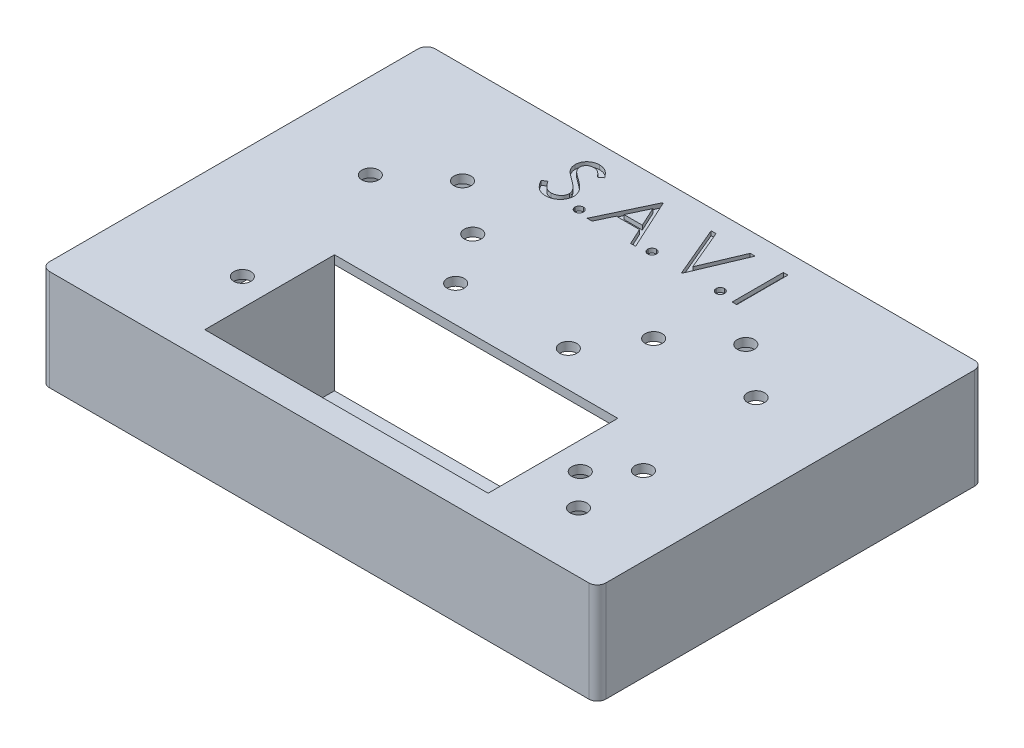
SolidWorks part; units mm, degrees
ref_plane "Front Plane" through (0, 0, 0) normal (0, 0, 1) x (1, 0, 0)
ref_plane "Top Plane" through (0, 0, 0) normal (0, 1, 0) x (1, 0, 0)
ref_plane "Right Plane" through (0, 0, 0) normal (1, 0, 0) x (0, 0, -1)
sketch "Sketch1" plane through (0, 0, 0) normal (0, 1, 0) x (1, 0, 0)
  line L1 (-81.5, 56.5) -> (81.5, 56.5)
  line L2 (-81.5, 56.5) -> (-81.5, -56.5)
  line L3 (-81.5, -56.5) -> (81.5, -56.5)
  line L4 (81.5, 56.5) -> (81.5, -56.5)
  line L5 (-81.5, 56.5) -> (81.5, -56.5) construction
  line L6 (-81.5, -56.5) -> (81.5, 56.5) construction
  point P0 (0, 0)
  dimension "D1" = 113
  dimension "D2" = 163
extrude "Boss-Extrude1" add sketch "Sketch1" along normal blind 29.5
fillet "Fillet1" radius 2.5 4 edges at (81.5, 14.75, -56.5) (-81.5, 14.75, -56.5) (-81.5, 14.75, 56.5) (81.5, 14.75, 56.5)
sketch "Sketch2" plane through (0, 0, 0) normal (0, -1, 0) x (1, 0, 0)
  line L1 (-77.5, 52.5) -> (77.5, 52.5)
  line L2 (-77.5, 52.5) -> (-77.5, -52.5)
  line L3 (-77.5, -52.5) -> (77.5, -52.5)
  line L4 (77.5, 52.5) -> (77.5, -52.5)
  line L5 (-77.5, 52.5) -> (77.5, -52.5) construction
  line L6 (-77.5, -52.5) -> (77.5, 52.5) construction
  point P0 (0, 0)
  dimension "D1" = 105
  dimension "D2" = 155
extrude "Cut-Extrude1" cut sketch "Sketch2" against normal blind 27
sketch "Sketch3" plane through (0, 27, 0) normal (0, -1, 0) x (1, 0, 0)
  line L0 (77.5, 52.5) -> (-77.5, 52.5) construction
  line L1 (-45.5, 48.5) -> (45.5, 48.5)
  line L2 (-45.5, 48.5) -> (-45.5, 10.5)
  line L3 (-45.5, 10.5) -> (45.5, 10.5)
  line L4 (45.5, 48.5) -> (45.5, 10.5)
  line L5 (-77.5, 52.5) -> (-77.5, -52.5) construction
  dimension "D1" = 4
  dimension "D2" = 38
  dimension "D3" = 91
  dimension "D4" = 32
extrude "Boss-Extrude4" add sketch "Sketch3" along normal blind 35
sketch "Sketch6" plane through (0, 0, 10.5) normal (0, 0, -1) x (-1, 0, 0)
  line L0 (45.5, 27) -> (-45.5, 27) construction
  line L1 (41.5, 27) -> (-41.5, 27)
  line L2 (41.5, 27) -> (41.5, -5)
  line L3 (41.5, -5) -> (-41.5, -5)
  line L4 (-41.5, 27) -> (-41.5, -5)
  line L5 (45.5, -8) -> (-45.5, -8) construction
  line L6 (45.5, -8) -> (45.5, 27) construction
  dimension "D1" = 83
  dimension "D2" = 3
  dimension "D3" = 4
extrude "Cut-Extrude2" cut sketch "Sketch6" against normal blind 39
sketch "Sketch7" plane through (0, 27, 0) normal (0, -1, 0) x (1, 0, 0)
  line L1 (-41.5, 10.5) -> (41.5, 10.5)
  line L2 (-41.5, 10.5) -> (-41.5, 48.5)
  line L3 (-41.5, 48.5) -> (41.5, 48.5)
  line L4 (41.5, 10.5) -> (41.5, 48.5)
extrude "Cut-Extrude3" cut sketch "Sketch7" against normal blind 3
sketch "Sketch8" plane through (0, 29.5, 0) normal (0, 1, 0) x (1, 0, 0)
  line L0 (-41.5, -10.5) -> (-41.5, -48.5) construction
  line L1 (41.5, -48.5) -> (41.5, -10.5) construction
  line L2 (41.5, -48.5) -> (41.5, -10.5) construction
  line L3 (41.5, -48.5) -> (-41.5, -48.5) construction
  line L4 (41.5, -10.5) -> (-41.5, -10.5) construction
  line L5 (41.5, -10.5) -> (-41.5, -10.5) construction
  circle A0 centre (-49.5, -29.5) radius 2.5
  circle A1 centre (49.5, -29.5) radius 2.5
  circle A2 centre (58.5, -20) radius 2.5
  circle A3 centre (58.5, -39) radius 2.5
  circle A4 centre (-16.5, 0) radius 2.5
  circle A5 centre (16.5, 0) radius 2.5
  circle A6 centre (-56.5, 15) radius 2.5
  circle A7 centre (-41.5, 27) radius 2.5
  circle A8 centre (-26.5, 15) radius 2.5
  circle A9 centre (41.5, 27) radius 2.5
  circle A10 centre (26.5, 15) radius 2.5
  circle A11 centre (56.5, 15) radius 2.5
  dimension "D1" = 5
  dimension "D2" = 5
  dimension "D7" = 5
  dimension "D8" = 5
  dimension "D16" = 5
  dimension "D17" = 5
  dimension "D18" = 5
  dimension "D19" = 5
  dimension "D20" = 5
  dimension "D21" = 5
  dimension "D22" = 5
  dimension "D23" = 5
  dimension "D3" = 8
  dimension "D4" = 8
  dimension "D5" = 17
  dimension "D6" = 17
  dimension "D9" = 9.5
  dimension "D10" = 19
  dimension "D11" = 19
  dimension "D12" = 19
  dimension "D13" = 9.5
  dimension "D14" = 25
  dimension "D15" = 25
  dimension "D24" = 15
  dimension "D25" = 15
  dimension "D26" = 15
  dimension "D27" = 15
  dimension "D28" = 15
  dimension "D29" = 12
  dimension "D30" = 15
  dimension "D31" = 15
  dimension "D32" = 12
  dimension "D33" = 15
  dimension "D34" = 37.5
extrude "Cut-Extrude5" cut sketch "Sketch8" against normal blind 2.5
sketch "Sketch9" plane through (0, 29.5, 0) normal (0, 1, 0) x (1, 0, 0)
  line L1 (-81.5, 54) -> (-81.5, -54) construction
  text T0 "S.A.V.I" font "Century Gothic" height 15
  dimension "D1" = 51
extrude "Cut-Extrude6" cut sketch "Sketch9" against normal blind 1.25
sketch "Sketch10" plane through (0, 0, 0) normal (0, -1, 0) x (-1, 0, 0)
  line L0 (61.5, -54.5) -> (58.5, -54.5) construction
  line L1 (61.5, -55.5) -> (58.5, -55.5)
  line L2 (61.5, -53.5) -> (58.5, -53.5)
  line L3 (-61.5, -54.5) -> (-58.5, -54.5) construction
  line L4 (-61.5, -53.5) -> (-58.5, -53.5)
  line L5 (-61.5, -55.5) -> (-58.5, -55.5)
  line L6 (61.5, 54.5) -> (58.5, 54.5) construction
  line L7 (61.5, 53.5) -> (58.5, 53.5)
  line L8 (61.5, 55.5) -> (58.5, 55.5)
  line L9 (-61.5, 54.5) -> (-58.5, 54.5) construction
  line L10 (-61.5, 55.5) -> (-58.5, 55.5)
  line L11 (-61.5, 53.5) -> (-58.5, 53.5)
  line L12 (81.5, 54) -> (81.5, -54) construction
  line L13 (79, -56.5) -> (-79, -56.5) construction
  line L15 (-81.5, -54) -> (-81.5, 54) construction
  line L17 (77.5, 52.5) -> (-77.5, 52.5) construction
  arc A0 (61.5, -55.5) -> (61.5, -53.5) centre (61.5, -54.5) ccw
  arc A1 (58.5, -53.5) -> (58.5, -55.5) centre (58.5, -54.5) ccw
  arc A2 (-61.5, -53.5) -> (-61.5, -55.5) centre (-61.5, -54.5) ccw
  arc A3 (-58.5, -55.5) -> (-58.5, -53.5) centre (-58.5, -54.5) ccw
  arc A4 (61.5, 53.5) -> (61.5, 55.5) centre (61.5, 54.5) ccw
  arc A5 (58.5, 55.5) -> (58.5, 53.5) centre (58.5, 54.5) ccw
  arc A6 (-61.5, 55.5) -> (-61.5, 53.5) centre (-61.5, 54.5) ccw
  arc A7 (-58.5, 53.5) -> (-58.5, 55.5) centre (-58.5, 54.5) ccw
  point P2 (60, -54.5)
  point P7 (-60, -54.5)
  point P14 (60, 54.5)
  point P21 (-60, 54.5)
  dimension "D3" = 1
  dimension "D5" = 1
  dimension "D10" = 1
  dimension "D11" = 1
  dimension "D12" = 1
  dimension "D14" = 20
  dimension "D1" = 20
  dimension "D2" = 3
  dimension "D4" = 1
  dimension "D6" = 3
  dimension "D7" = 20
  dimension "D8" = 20
  dimension "D9" = 3
  dimension "D13" = 3
extrude "Cut-Extrude7" cut sketch "Sketch10" against normal blind 3
